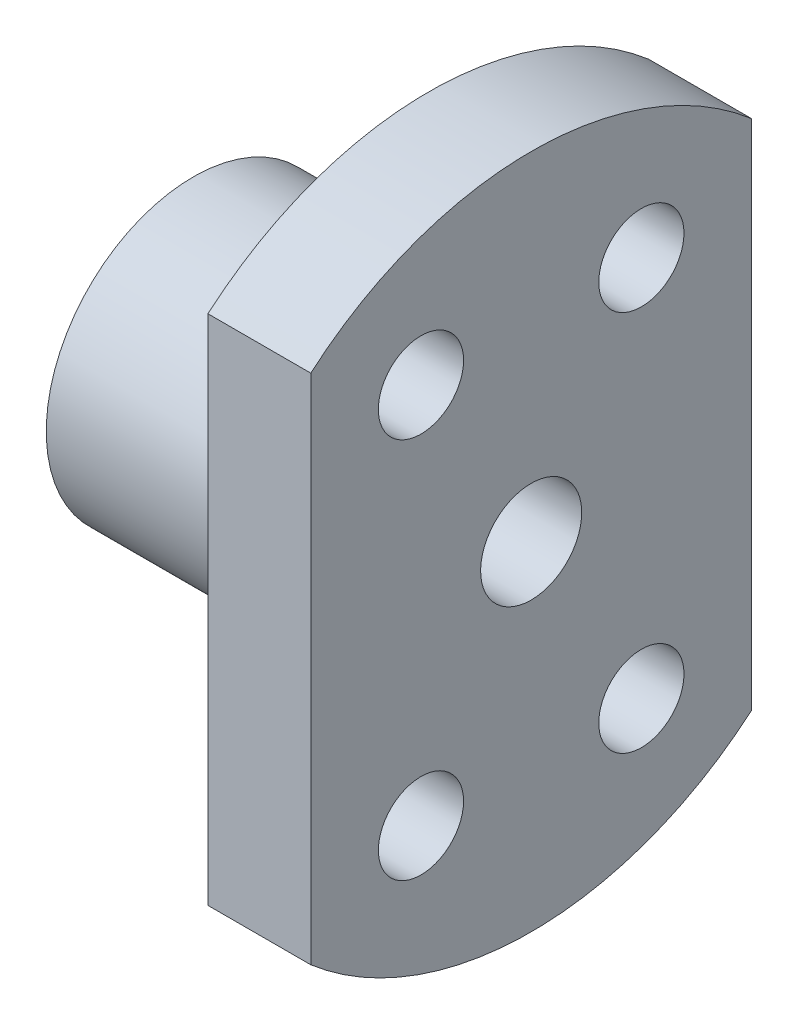
SolidWorks part; units mm, degrees
ref_plane "前视基准面" through (0, 0, 0) normal (0, 0, 1) x (1, 0, 0)
ref_plane "上视基准面" through (0, 0, 0) normal (0, 1, 0) x (1, 0, 0)
ref_plane "右视基准面" through (0, 0, 0) normal (1, 0, 0) x (0, 0, -1)
sketch "草图2" plane through (0, 0, 0) normal (0, 0, 1) x (1, 0, 0)
  line L0 (-5.75, 0) -> (-5.75, 5)
  line L1 (-5.75, 5) -> (2.25, 5)
  line L2 (2.25, 5) -> (2.25, 11.5)
  line L3 (2.25, 11.5) -> (5.75, 11.5)
  line L4 (5.75, 11.5) -> (5.75, 0)
  line L5 (5.75, 0) -> (-5.75, 0)
  dimension "D1" = 3.5
  dimension "D2" = 11.5
  dimension "D3" = 11.5
  dimension "D4" = 5
revolve "旋转1" add sketch "草图2" angle 360 about L5
sketch "草图3" plane through (-5.75, 0, 0) normal (-1, 0, 0) x (0, 0, 1)
  circle A0 centre (0, 0) radius 1.72
  dimension "D1" = 3.44
extrude "切除-拉伸1" cut sketch "草图3" against normal through all
cosmetic thread "装饰螺纹线1" parameters "D2"=4
sketch "草图5" plane through (5.75, 0, 0) normal (1, 0, 0) x (0, 0, -1)
  line L0 (-3.75, -6.4952) -> (3.75, 6.4952) construction
  line L1 (-3.75, 6.4952) -> (3.75, -6.4952) construction
  line L2 (0, 0) -> (0, 7.5) construction
  circle A0 centre (-3.75, 6.4952) radius 1.45
  circle A1 centre (3.75, 6.4952) radius 1.45
  circle A2 centre (-3.75, -6.4952) radius 1.45
  circle A3 centre (3.75, -6.4952) radius 1.45
  circle A4 centre (0, 0) radius 7.5 construction
  dimension "D3" = 15
  dimension "D4" = 2.9
  dimension "D1" = 30
  dimension "D2" = 30
extrude "切除-拉伸2" cut sketch "草图5" against normal through all
sketch "草图6" plane through (5.75, 0, 0) normal (1, 0, 0) x (0, 0, -1)
  line L1 (-7.5, -11.5) -> (7.5, -11.5)
  line L2 (-7.5, -11.5) -> (-7.5, 11.5)
  line L3 (-7.5, 11.5) -> (7.5, 11.5)
  line L4 (7.5, -11.5) -> (7.5, 11.5)
  line L5 (-7.5, -11.5) -> (7.5, 11.5) construction
  line L6 (-7.5, 11.5) -> (7.5, -11.5) construction
  circle A0 centre (0, 0) radius 11.5 construction
  point P0 (0, 0)
  dimension "D1" = 15
extrude "切除-拉伸3" cut sketch "草图6" against normal through all flip side to cut
